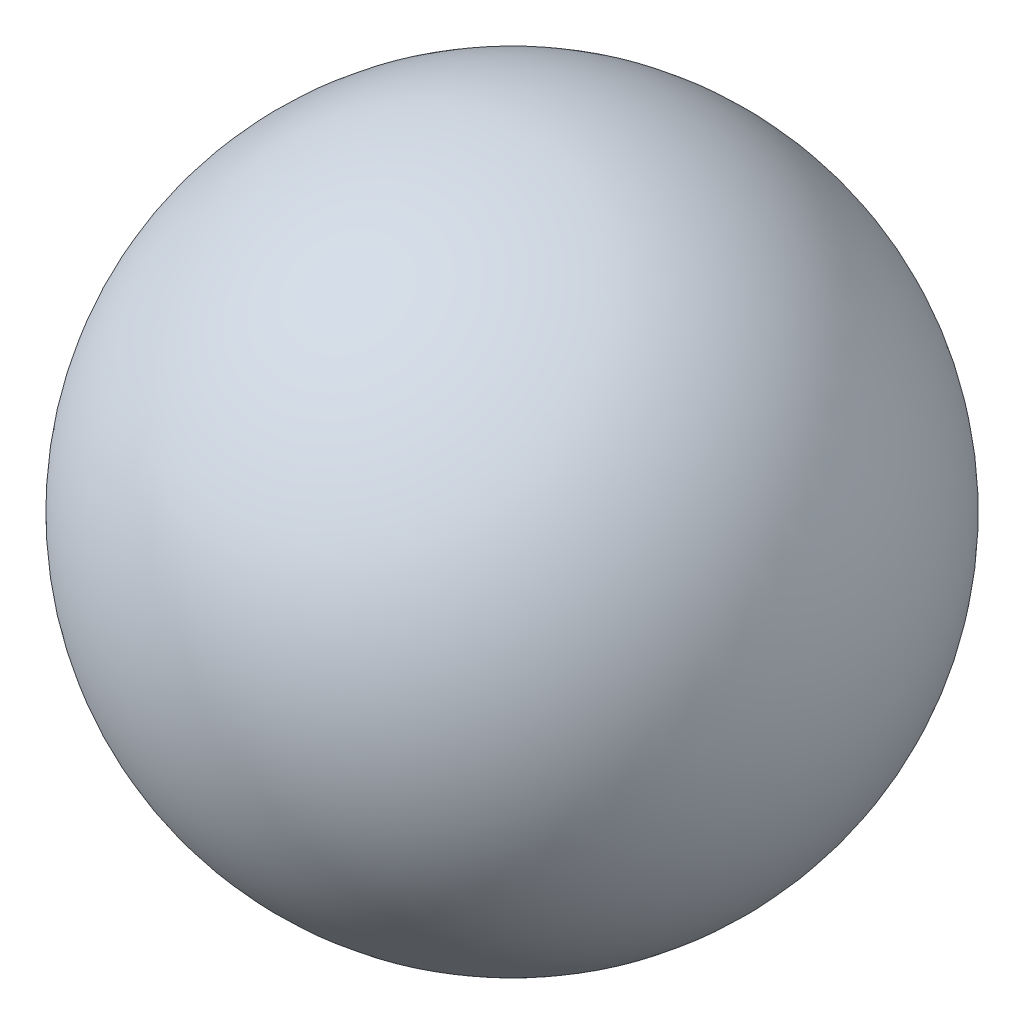
SolidWorks part; units mm, degrees
material "Acero al carbono no aleado"
ref_plane "Alzado" through (0, 0, 0) normal (0, 0, 1) x (1, 0, 0)
ref_plane "Planta" through (0, 0, 0) normal (0, 1, 0) x (1, 0, 0)
ref_plane "Vista lateral" through (0, 0, 0) normal (1, 0, 0) x (0, 0, -1)
sketch "Croquis1" plane through (0, 0, 0) normal (0, 0, 1) x (1, 0, 0)
  line L0 (0, 1.5) -> (0, 0)
  arc A0 (0, 0) -> (0, 1.5) centre (0, 0.75) ccw
  dimension "D1" = 0.75
  dimension "D2" = 1.5
revolve "Revolución1" add sketch "Croquis1" angle 360 about L0
